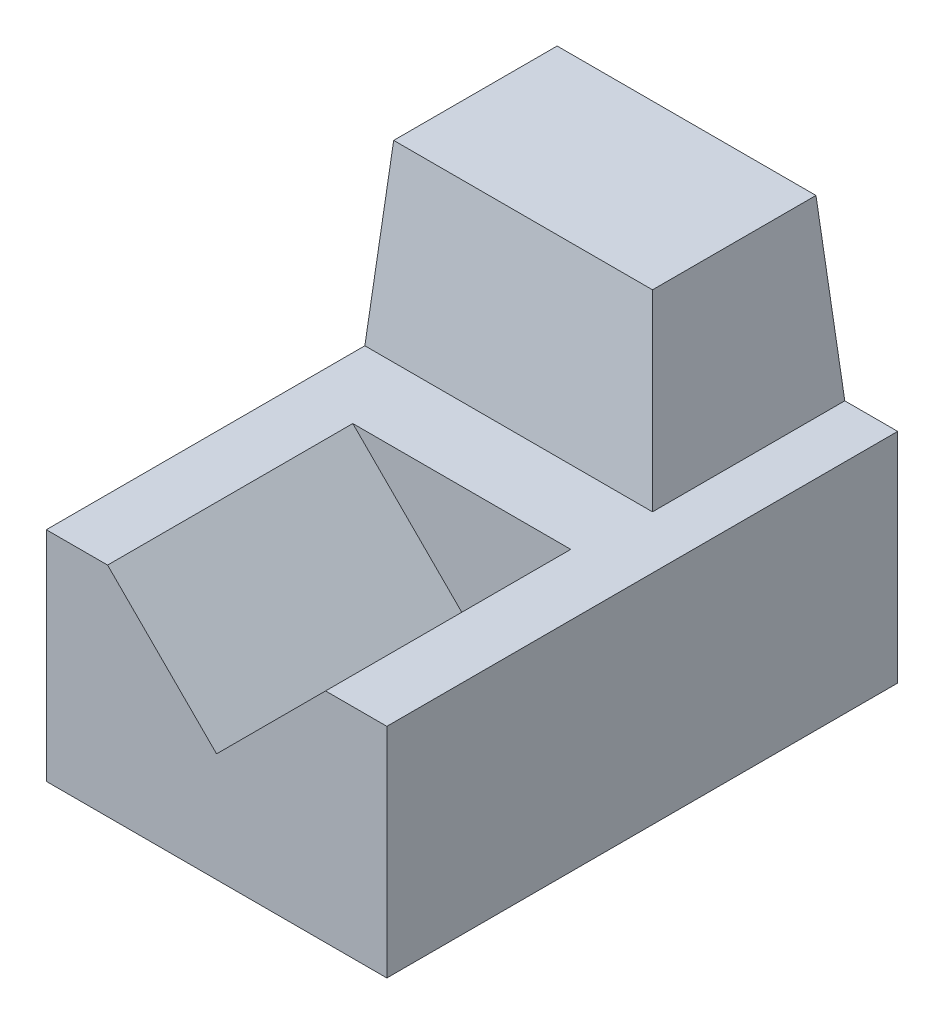
SolidWorks part; units mm, degrees
ref_plane "Front Plane" through (0, 0, 0) normal (0, 0, 1) x (1, 0, 0)
ref_plane "Top Plane" through (0, 0, 0) normal (0, 1, 0) x (1, 0, 0)
ref_plane "Right Plane" through (0, 0, 0) normal (1, 0, 0) x (0, 0, -1)
sketch "Sketch1" plane through (0, 0, 0) normal (0, 1, 0) x (1, 0, 0)
  line L1 (-25, 37.5) -> (25, 37.5)
  line L2 (-25, 37.5) -> (-25, -37.5)
  line L3 (-25, -37.5) -> (25, -37.5)
  line L4 (25, 37.5) -> (25, -37.5)
  line L5 (-25, 37.5) -> (25, -37.5) construction
  line L6 (-25, -37.5) -> (25, 37.5) construction
  point P0 (0, 0)
  dimension "D1" = 75
  dimension "D2" = 50
extrude "Boss-Extrude1" add sketch "Sketch1" along normal mid plane 32
sketch "Sketch2" plane through (0, 0, 37.5) normal (0, 0, 1) x (1, 0, 0)
  line L0 (0, 0) -> (-16, 16)
  line L1 (-25, 16) -> (25, 16) construction
  line L2 (-16, 16) -> (16, 16)
  line L3 (16, 16) -> (0, 0)
  line L4 (-25, 16) -> (-25, -16) construction
  line L5 (25, 16) -> (25, -16) construction
  line L6 (-25, -16) -> (25, -16) construction
  dimension "D1" = 32
  dimension "D2" = 9
  dimension "D3" = 9
  dimension "D4" = 16
  dimension "D5" = 25
extrude "Cut-Extrude1" cut sketch "Sketch2" against normal blind 36
sketch "Sketch3" plane through (0, 16, 0) normal (0, 1, 0) x (1, 0, 0)
  line L0 (13, 37.5) -> (13, 13.5)
  line L1 (25, 37.5) -> (-25, 37.5) construction
  line L2 (13, 13.5) -> (-25, 13.5)
  line L3 (-25, 37.5) -> (-25, -37.5) construction
  line L4 (-25, 13.5) -> (-25, 37.5)
  line L5 (25, -37.5) -> (25, 37.5) construction
  line L6 (-25, 37.5) -> (13, 37.5)
  dimension "D1" = 12
  dimension "D2" = 24
extrude "Boss-Extrude4" add sketch "Sketch3" along normal blind 24
draft "Draft2" type of draft neutral plane draft angle 10 faces to draft 2 face at (13, 28, -25.5) face at (-6, 28, -13.5) neutral plane through (0, 40, 0) neutral plane normal (0, 1, 0) parameters "D1"=10
